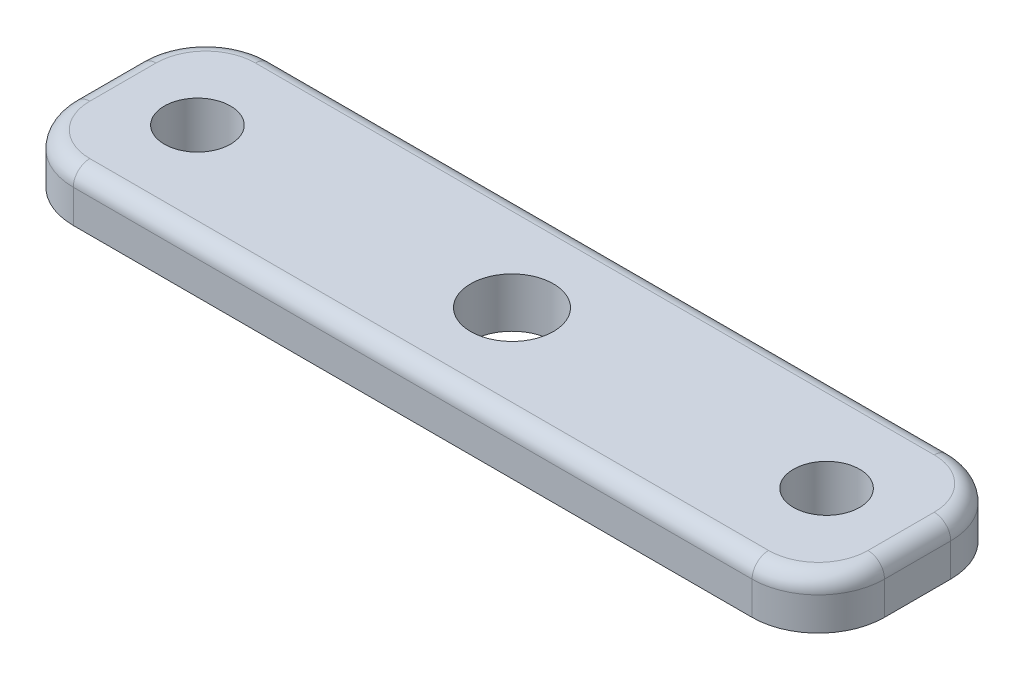
SolidWorks part; units mm, degrees
ref_plane "Front Plane" through (0, 0, 0) normal (0, 0, 1) x (1, 0, 0)
ref_plane "Top Plane" through (0, 0, 0) normal (0, 1, 0) x (1, 0, 0)
ref_plane "Right Plane" through (0, 0, 0) normal (1, 0, 0) x (0, 0, -1)
sketch "Sketch1" plane through (0, 0, 0) normal (0, 1, 0) x (1, 0, 0)
  line L9 (-5.5, 2) -> (-5.5, -2)
  line L10 (-1.5, 6) -> (39.5, 6)
  line L12 (-1.5, -6) -> (39.5, -6)
  line L14 (43.5, 2) -> (43.5, -2)
  circle A0 centre (0, 0) radius 2
  circle A1 centre (38, 0) radius 2
  arc A2 (39.5, 6) -> (43.5, 2) centre (39.5, 2) cw
  arc A3 (43.5, -2) -> (39.5, -6) centre (39.5, -2) cw
  arc A4 (-1.5, -6) -> (-5.5, -2) centre (-1.5, -2) cw
  arc A5 (-1.5, 6) -> (-5.5, 2) centre (-1.5, 2) ccw
  circle A6 centre (19.0503, -0.0503) radius 2.5
  dimension "D1" = 4
extrude "Boss-Extrude1" add sketch "Sketch1" along normal blind 3
fillet "Fillet1" radius 1 8 edges at (-4.3284, 3, 4.8284) (-5.5, 3, 0) (-4.3284, 3, -4.8284) (19, 3, -6) (42.3284, 3, -4.8284) (43.5, 3, 0) (42.3284, 3, 4.8284) (19, 3, 6)
